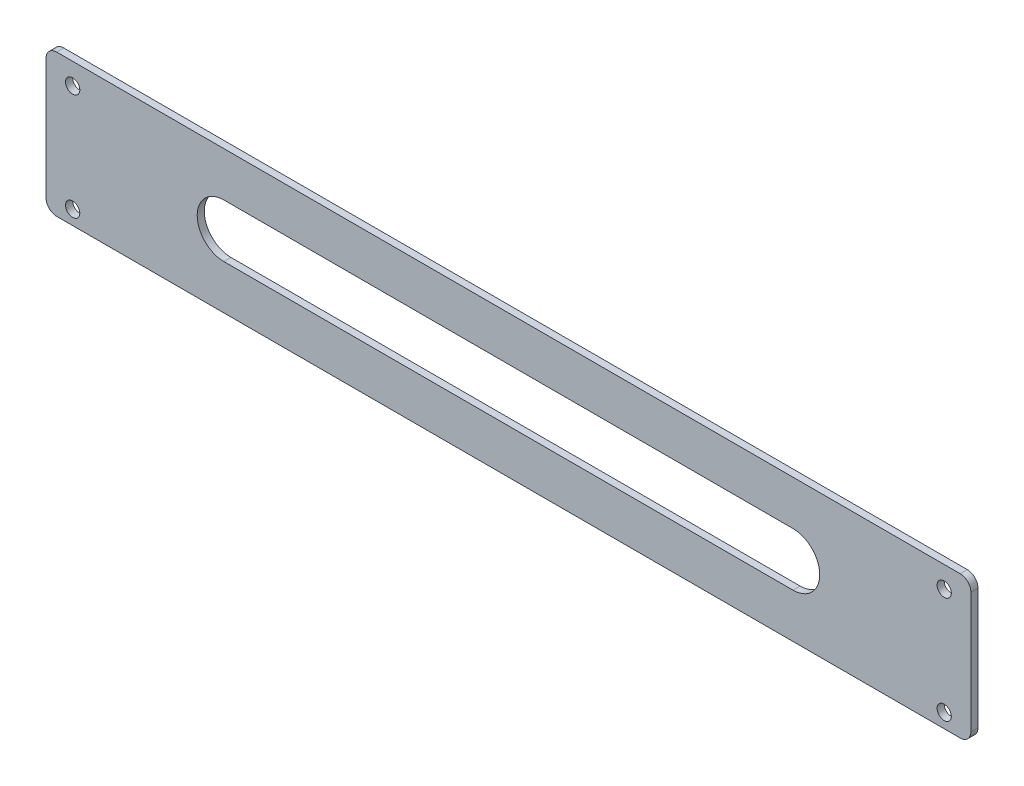
SolidWorks part; units mm, degrees
ref_plane "前视基准面" through (0, 0, 0) normal (0, 0, 1) x (1, 0, 0)
ref_plane "上视基准面" through (0, 0, 0) normal (0, 1, 0) x (1, 0, 0)
ref_plane "右视基准面" through (0, 0, 0) normal (1, 0, 0) x (0, 0, -1)
sketch "草图1" plane through (0, 0, 0) normal (0, 0, 1) x (1, 0, 0)
  line L1 (-130, 20) -> (130, 20)
  line L2 (-130, 20) -> (-130, -20)
  line L3 (-130, -20) -> (130, -20)
  line L4 (130, 20) -> (130, -20)
  line L5 (-130, 20) -> (130, -20) construction
  line L6 (-130, -20) -> (130, 20) construction
  point P0 (0, 0)
  dimension "D1" = 40
  dimension "D2" = 260
extrude "凸台-拉伸1" add sketch "草图1" along normal blind 2
sketch "草图3" plane through (0, 0, 2) normal (0, 0, 1) x (1, 0, 0)
  line L0 (-130, 20) -> (-130, -20) construction
  line L1 (130, 20) -> (-130, 20) construction
  line L2 (-130, -20) -> (130, -20) construction
  line L3 (0, 53.0401) -> (0, -67.1883) construction
  circle A0 centre (-122.5, 14) radius 2
  circle A1 centre (-122.5, -16) radius 2
  circle A2 centre (122.5, -16) radius 2
  circle A3 centre (122.5, 14) radius 2
  dimension "D1" = 7.5
  dimension "D2" = 4
  dimension "D3" = 6
  dimension "D4" = 4
extrude "切除-拉伸2" cut sketch "草图3" against normal blind 2
sketch "草图4" plane through (0, 0, 2) normal (0, 0, 1) x (1, 0, 0)
  line L0 (-80, 0) -> (80, 0) construction
  line L1 (-80, 7.5) -> (80, 7.5)
  line L2 (-80, -7.5) -> (80, -7.5)
  arc A0 (-80, 7.5) -> (-80, -7.5) centre (-80, 0) ccw
  arc A1 (80, -7.5) -> (80, 7.5) centre (80, 0) ccw
  point P3 (0, 0)
  dimension "D1" = 15
  dimension "D2" = 160
extrude "切除-拉伸3" cut sketch "草图4" against normal through all
fillet "圆角1" radius 3 4 edges at (130, -20, 1) (-130, -20, 1) (130, 20, 1) (-130, 20, 1)
